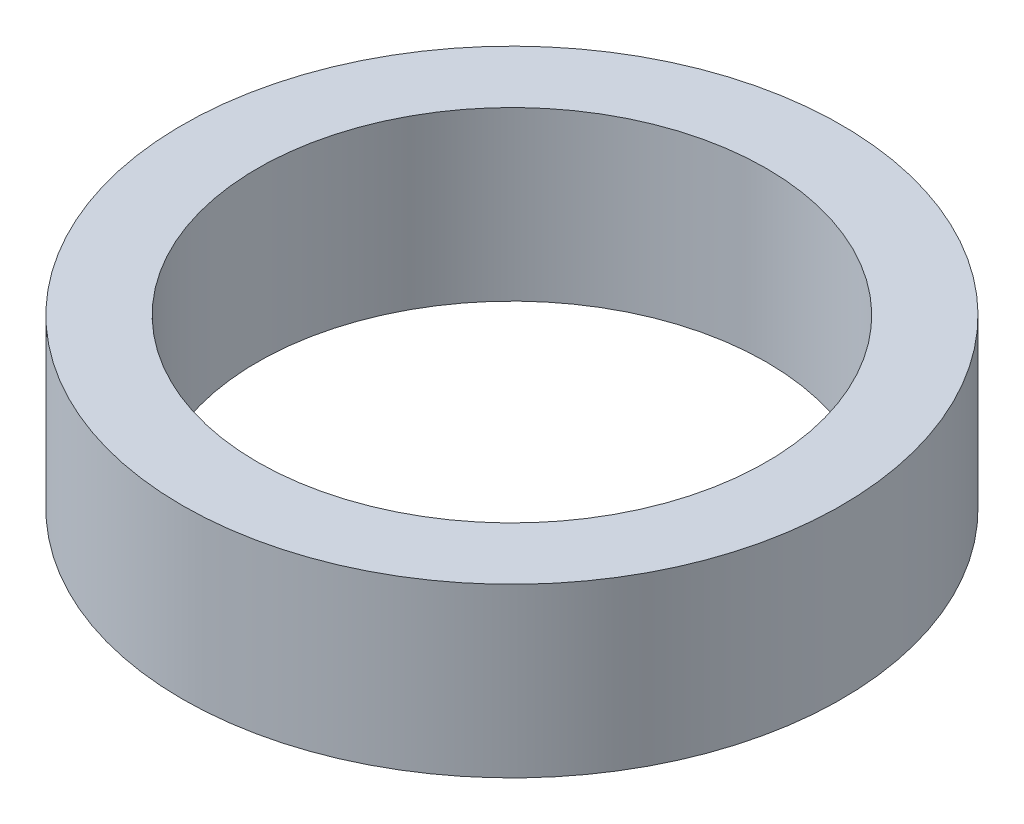
SolidWorks part; units mm, degrees
ref_plane "Front Plane" through (0, 0, 0) normal (0, 0, 1) x (1, 0, 0)
ref_plane "Top Plane" through (0, 0, 0) normal (0, 1, 0) x (1, 0, 0)
ref_plane "Right Plane" through (0, 0, 0) normal (1, 0, 0) x (0, 0, -1)
sketch "Sketch1" plane through (0, 0, 0) normal (0, 1, 0) x (1, 0, 0)
  circle A0 centre (0, 0) radius 28.5
  circle A1 centre (0, 0) radius 22
  dimension "D1" = 44
  dimension "D2" = 57
sketch "Sketch2" plane through (0, 0, 0) normal (0, 1, 0) x (1, 0, 0)
extrude "Boss-Extrude1" add sketch "Sketch1" along normal blind 14.5
